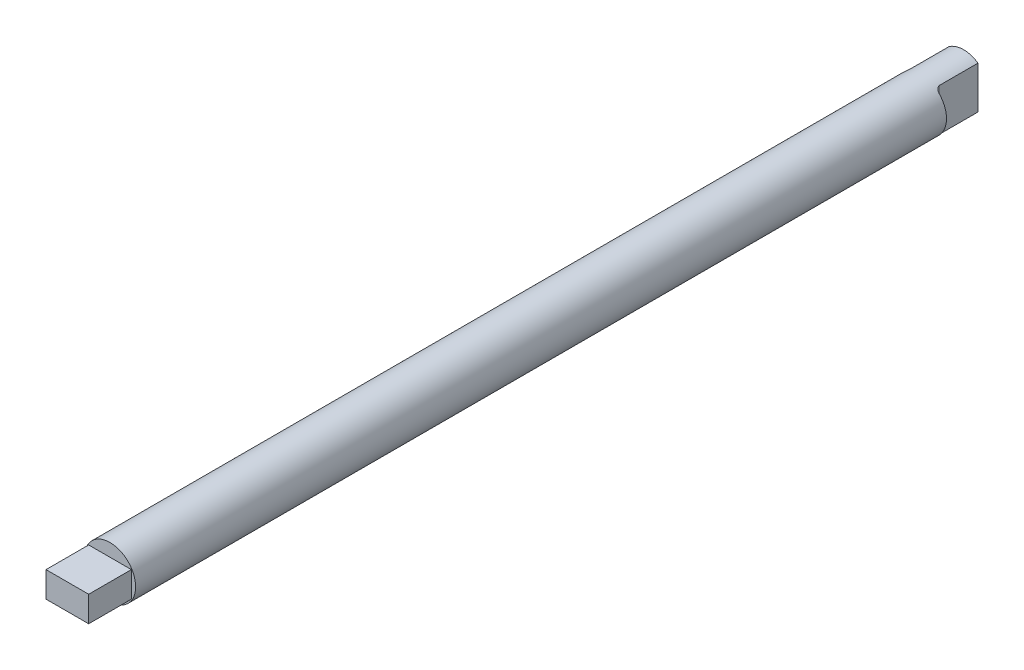
SolidWorks part; units mm, degrees
ref_plane "Piano frontale" through (0, 0, 0) normal (0, 0, 1) x (1, 0, 0)
ref_plane "Piano superiore" through (0, 0, 0) normal (0, 1, 0) x (1, 0, 0)
ref_plane "Piano destro" through (0, 0, 0) normal (1, 0, 0) x (0, 0, -1)
sketch "Schizzo1" plane through (0, 0, 0) normal (0, 0, 1) x (1, 0, 0)
  circle A0 centre (0, 0) radius 6
  point P3 (0, 0)
extrude "Estrusione-Estrusione1" add sketch "Schizzo1" along normal blind 200
sketch "Schizzo2" plane through (0, 0, 200) normal (0, 0, 1) x (1, 0, 0)
  line L1 (-5, 3) -> (5, 3)
  line L2 (-5, 3) -> (-5, -3)
  line L3 (-5, -3) -> (5, -3)
  line L4 (5, 3) -> (5, -3)
  line L5 (-5, 3) -> (5, -3) construction
  line L6 (-5, -3) -> (5, 3) construction
  point P0 (0, 0)
  dimension "D1" = 6
  dimension "D2" = 10
extrude "Estrusione-Estrusione2" add sketch "Schizzo2" along normal blind 10
sketch "Schizzo6" plane through (0, 0, 0) normal (0, 0, -1) x (-1, 0, 0)
  line L0 (0, 5.9699) -> (0, -6) construction
  line L1 (6, 6.6775) -> (6, -6)
  line L2 (3.3746, 6.6775) -> (6, 6.6775)
  line L3 (3.3746, -6) -> (3.3746, 6.6775)
  line L4 (0, -6) -> (-6.7491, -6) construction
  line L5 (-3.3746, -6) -> (-3.3746, 6.6775)
  line L6 (-3.3746, 6.6775) -> (-6, 6.6775)
  line L7 (-6, 6.6775) -> (-6, -6)
  line L8 (-6, -6) -> (-3.3746, -6)
  line L13 (6, -6) -> (3.3746, -6)
  circle A1 centre (0, 0) radius 6 construction
extrude "Taglio-Estrusione1" cut sketch "Schizzo6" against normal blind 10
fillet "Raccordo2" radius 1 1 edges at (3.3746, 0, 10)
fillet "Raccordo3" radius 1 1 edges at (-3.3746, 0, 10)
